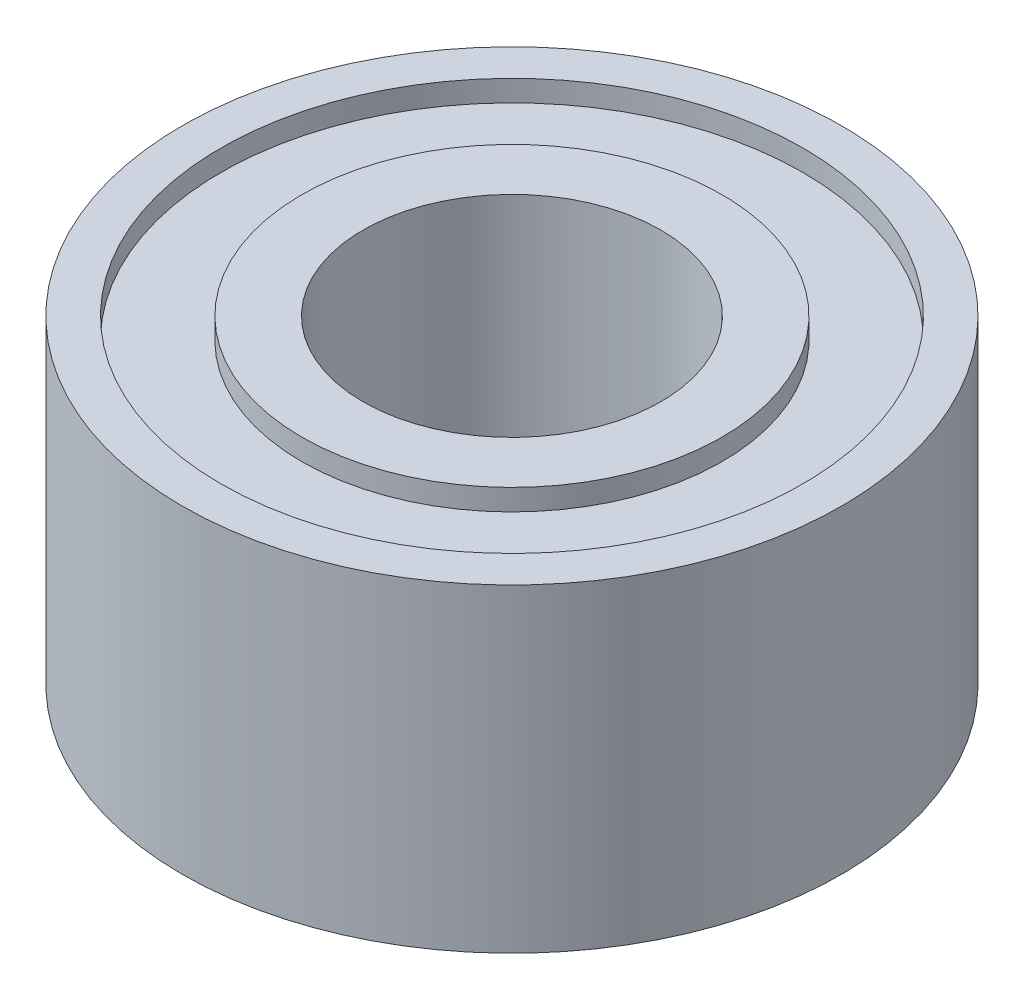
SolidWorks part; units mm, degrees
ref_plane "Front Plane" through (0, 0, 0) normal (0, 0, 1) x (1, 0, 0)
ref_plane "Top Plane" through (0, 0, 0) normal (0, 1, 0) x (1, 0, 0)
ref_plane "Right Plane" through (0, 0, 0) normal (1, 0, 0) x (0, 0, -1)
sketch "Sketch1" plane through (0, 0, 0) normal (0, 1, 0) x (1, 0, 0)
  circle A0 centre (0, 0) radius 15.5
  circle A1 centre (0, 0) radius 7
  dimension "D1" = 31
  dimension "D2" = 14
extrude "Boss-Extrude1" add sketch "Sketch1" along normal blind 15
sketch "Sketch5" plane through (0, 15, 0) normal (0, 1, 0) x (1, 0, 0)
  circle A0 centre (0, 0) radius 9.8795
  circle A1 centre (0, 0) radius 13.6843
extrude "Cut-Extrude3" cut sketch "Sketch5" against normal blind 1
sketch "Sketch6" plane through (0, 0, 0) normal (0, -1, 0) x (1, 0, 0)
  circle A1 centre (0, 0) radius 13.6843
  circle A2 centre (0, 0) radius 13.6843
  circle A3 centre (0, 0) radius 9.8795
  circle A4 centre (0, 0) radius 9.8795
  dimension "D1" = 0
  dimension "D2" = 0
extrude "Cut-Extrude4" cut sketch "Sketch6" against normal blind 1
